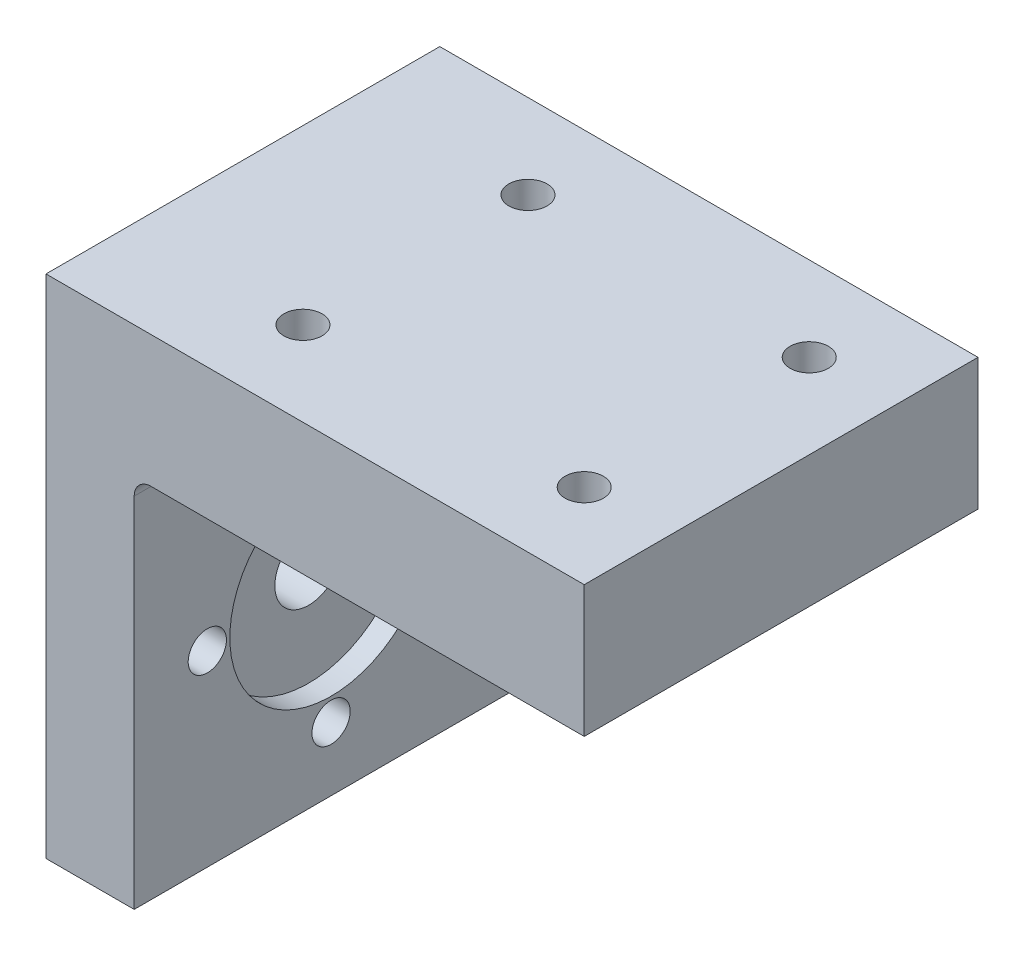
SolidWorks part; units mm, degrees
ref_plane "Front Plane" through (0, 0, 0) normal (1, 0, 0) x (0, 1, 0)
ref_plane "Top Plane" through (0, 0, 0) normal (0, 0, 1) x (0, 1, 0)
ref_plane "Right Plane" through (0, 0, 0) normal (0, 1, 0) x (-1, 0, 0)
sketch "Sketch3" plane through (0, 0, 0) normal (1, 0, 0) x (0, 1, 0)
  line L1 (-22.5, 17.5) -> (22.5, 17.5)
  line L2 (-22.5, 17.5) -> (-22.5, -17.5)
  line L3 (-22.5, -17.5) -> (22.5, -17.5)
  line L4 (22.5, 17.5) -> (22.5, -17.5)
  line L5 (-22.5, 17.5) -> (22.5, -17.5) construction
  line L6 (-22.5, -17.5) -> (22.5, 17.5) construction
  point P0 (0, 0)
  dimension "D1" = 45
  dimension "D2" = 35
extrude "Boss-Extrude1" add sketch "Sketch3" against normal blind 7.8384
sketch "Sketch10" plane through (0, 0, 0) normal (1, 0, 0) x (0, 1, 0)
  line L0 (-22.5, -17.5) -> (22.5, -17.5) construction
  line L1 (22.5, 17.5) -> (10.8151, 17.5)
  line L2 (22.5, 17.5) -> (22.5, -17.5)
  line L3 (22.5, -17.5) -> (10.8151, -17.5)
  line L4 (10.8151, 17.5) -> (10.8151, -17.5)
  dimension "D1" = 11.6849
extrude "Boss-Extrude3" add sketch "Sketch10" along normal blind 40
sketch "Sketch12" plane through (0, 0, 0) normal (1, 0, 0) x (0, 1, 0)
  line L0 (-5.8424, 17.5) -> (-5.8424, -17.5) construction
  line L1 (10.8151, 17.5) -> (-22.5, 17.5) construction
  line L2 (-22.5, -17.5) -> (10.8151, -17.5) construction
  circle A0 centre (-5.8424, 0) radius 3
  circle A1 centre (-5.8424, 0) radius 11 construction
  circle A2 centre (-5.8424, 11) radius 1.7
  circle A3 centre (-16.8424, 0) radius 1.7
  circle A4 centre (-5.8424, -11) radius 1.7
  circle A5 centre (5.1576, 0) radius 1.7
  dimension "D1" = 6
  dimension "D2" = 22
  dimension "D3" = 3.4
  dimension "D4" = 4
extrude "Cut-Extrude5" cut sketch "Sketch12" against normal through all
sketch "Sketch13" plane through (0, 0, 0) normal (1, 0, 0) x (0, 1, 0)
  circle A0 centre (-5.8424, 0) radius 9
  dimension "D1" = 18
extrude "Cut-Extrude6" cut sketch "Sketch13" against normal blind 2
sketch "Sketch14" plane through (0, 10.8151, 0) normal (0, -1, 0) x (1, 0, 0)
  line L0 (20, 17.5) -> (20, -17.5) construction
  line L1 (40, 17.5) -> (0, 17.5) construction
  line L2 (40, -17.5) -> (0, -17.5) construction
  line L3 (40, 17.5) -> (40, -17.5) construction
  line L4 (0, 17.5) -> (0, -17.5) construction
  circle A0 centre (7.5, 10) radius 1.7
  circle A1 centre (32.5, 10) radius 1.7
  circle A2 centre (7.5, -10) radius 1.7
  circle A3 centre (32.5, -10) radius 1.7
  dimension "D1" = 3.4
  dimension "D2" = 7.5
  dimension "D3" = 7.5
  dimension "D4" = 7.5
  dimension "D5" = 7.5
  dimension "D6" = 7.5
  dimension "D7" = 7.5
  dimension "D8" = 7.5
  dimension "D9" = 7.5
  dimension "D10" = 3.4
  dimension "D11" = 3.4
  dimension "D12" = 3.4
extrude "Cut-Extrude7" cut sketch "Sketch14" against normal through all
fillet "Fillet2" radius 1.5 1 edges at (0, 10.8151, 0)
equation "\"Force\"= 300"
equation "\"Safety Factor\"= 3"
equation "\"Safety Factor Force\"= \"Force\" * \"Safety Factor\""
equation "\"Shaft Length\"= 18"
equation "\"Base\"= 35"
equation "\"Length1\"= 45"
equation "\"Length2\"= 40"
equation "\"Yield Strength\"= 45.2"
equation "\"Moment1\"= \"Safety Factor Force\" * \"Shaft Length\""
equation "\"Height1\"= sqr ( ( 6 * \"Moment1\" ) / ( \"Base\" * \"Yield Strength\" ) )"
equation "\"Moment2\"= \"Safety Factor Force\" * \"Length2\""
equation "\"Height2\"= SQR ( ( 6 * \"Moment2\" ) / ( \"Base\" * \"Yield Strength\" ) )"
equation "\"D1@Sketch3\"=\"Length1\""
equation "\"D2@Sketch3\"=\"Base\""
equation "\"D1@Boss-Extrude1\"=\"Height1\""
equation "\"D1@Sketch10\"=\"Height2\""
equation "\"D1@Boss-Extrude3\"=\"Length2\""
equation "\"D1@Sketch13\"=\"Shaft Length\""
